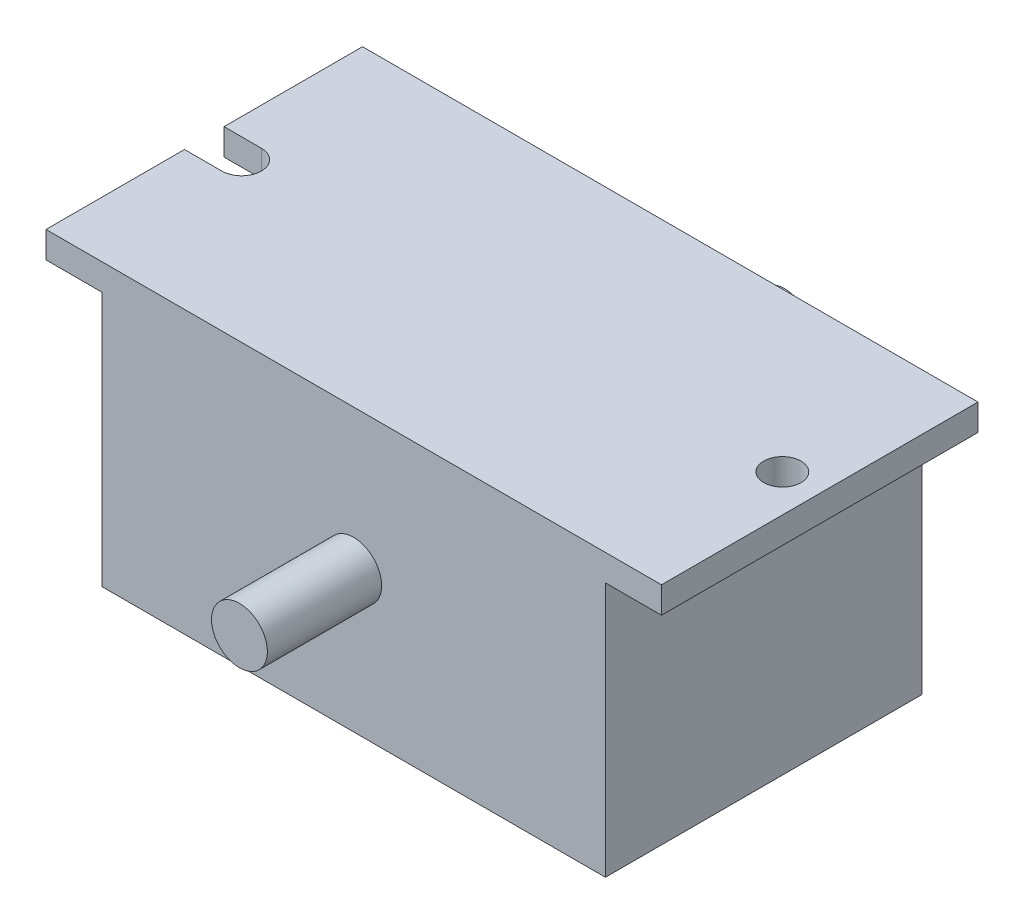
SolidWorks part; units mm, degrees
ref_plane "Front Plane" through (0, 0, 0) normal (0, 0, 1) x (1, 0, 0)
ref_plane "Top Plane" through (0, 0, 0) normal (0, 1, 0) x (1, 0, 0)
ref_plane "Right Plane" through (0, 0, 0) normal (1, 0, 0) x (0, 0, -1)
sketch "Sketch1" plane through (0, 0, 0) normal (0, 0, 1) x (1, 0, 0)
  line L1 (-57.25, 32) -> (57.25, 32)
  line L2 (-57.25, 26) -> (-57.25, -32)
  line L3 (-57.25, -32) -> (57.25, -32)
  line L4 (57.25, 26) -> (57.25, -32)
  line L5 (-57.25, 32) -> (57.25, -32) construction
  line L6 (-57.25, -32) -> (57.25, 32) construction
  line L7 (70, 32) -> (70, 26)
  line L8 (70, 26) -> (57.25, 26)
  line L9 (-57.25, 32) -> (-70, 32)
  line L10 (-70, 32) -> (-70, 26)
  line L11 (-70, 26) -> (-57.25, 26)
  line L12 (57.25, 32) -> (70, 32)
  point P0 (0, 0)
  point P14 (-10.8339, 38.269)
  dimension "D1" = 114.5
  dimension "D2" = 64
  dimension "D3" = 70
  dimension "D4" = 70
  dimension "D5" = 6
  dimension "D6" = 6
  dimension "D7" = 12.75
  dimension "D8" = 114.5
extrude "Boss-Extrude1" add sketch "Sketch1" along normal blind 72
sketch "Sketch2" plane through (0, 32, 0) normal (0, 1, 0) x (1, 0, 0)
  line L0 (-61.5, -31.5) -> (-70, -31.5)
  line L1 (-70, -72) -> (-70, 0) construction
  line L2 (-61.5, -40.5) -> (-70, -40.5)
  line L3 (-70, -31.5) -> (-70, -40.5)
  circle A0 centre (61.5, -36) radius 4.25
  arc A1 (-61.5, -40.5) -> (-61.5, -31.5) centre (-61.5, -36) ccw
  dimension "D3" = 8.5
  dimension "D6" = 9
  dimension "D1" = 61.5
  dimension "D2" = 36
  dimension "D4" = 36
  dimension "D5" = 61.5
extrude "Cut-Extrude1" cut sketch "Sketch2" against normal through all
sketch "Sketch3" plane through (0, 0, 72) normal (0, 0, 1) x (1, 0, 0)
  circle A0 centre (0, 0) radius 6.35
  dimension "D1" = 12.7
extrude "Boss-Extrude2" add sketch "Sketch3" along normal blind 26
sketch "Sketch5" plane through (0, 0, 0) normal (0, 0, -1) x (-1, 0, 0)
  circle A0 centre (0, 0) radius 6.35
  dimension "D1" = 12.7
extrude "Boss-Extrude3" add sketch "Sketch5" along normal blind 26
